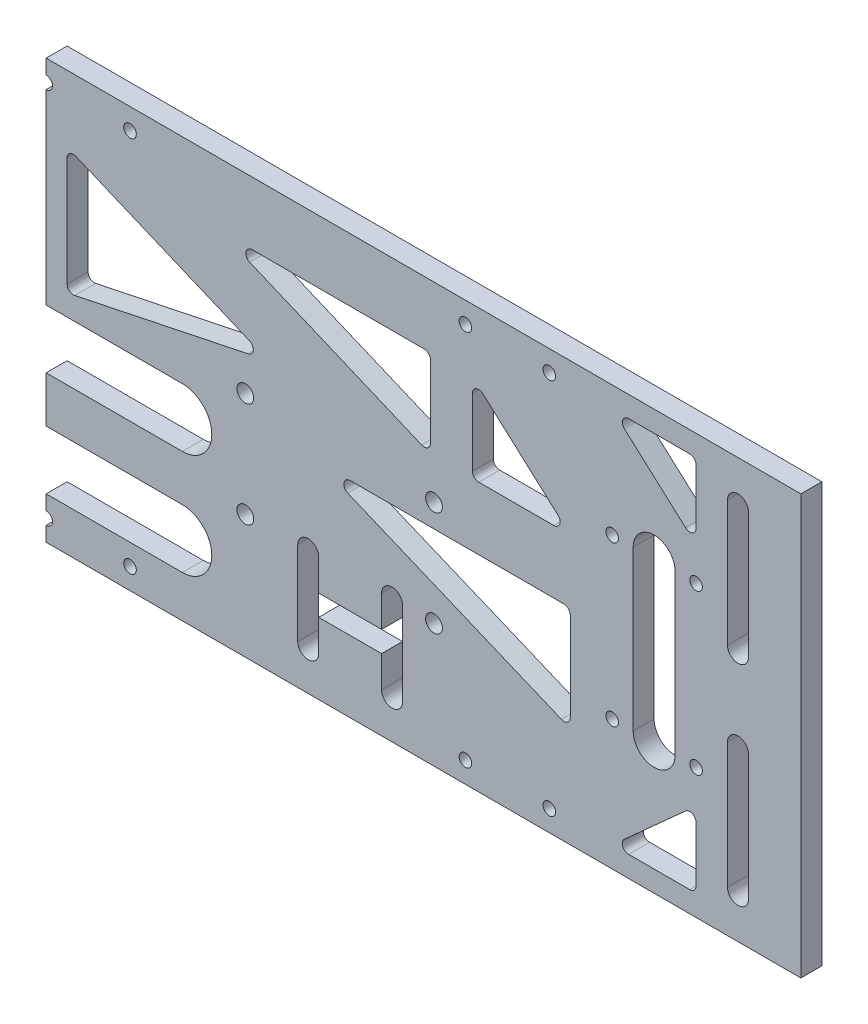
SolidWorks part; units mm, degrees
material "A-玻璃纤维"
ref_plane "前视基准面" through (0, 0, 0) normal (0, 0, 1) x (1, 0, 0)
ref_plane "上视基准面" through (0, 0, 0) normal (0, 1, 0) x (1, 0, 0)
ref_plane "右视基准面" through (0, 0, 0) normal (1, 0, 0) x (0, 0, -1)
sketch "草图1" plane through (0, 0, 0) normal (0, 0, 1) x (1, 0, 0)
  line L1 (0, 0) -> (320, 0)
  line L2 (0, 0) -> (0, 121)
  line L3 (0, 121) -> (320, 121)
  line L4 (320, 0) -> (320, 121)
  dimension "D1" = 320
  dimension "D2" = 121
extrude "凸台-拉伸1" add sketch "草图1" along normal blind 5
sketch "草图2" plane through (0, 0, 5) normal (0, 0, 1) x (1, 0, 0)
  line L0 (160, 121) -> (160, 0) construction
  line L1 (320, 121) -> (0, 121) construction
  line L2 (0, 0) -> (320, 0) construction
  line L3 (0, 121) -> (0, 0) construction
  line L4 (30, 0) -> (35, 0)
  line L5 (30, 0) -> (30, 30)
  line L6 (30, 30) -> (35, 30)
  line L7 (35, 0) -> (35, 30)
  line L8 (285, 0) -> (285, 30)
  line L9 (290, 30) -> (285, 30)
  line L10 (290, 0) -> (290, 30)
  line L11 (290, 0) -> (285, 0)
  dimension "D1" = 30
  dimension "D2" = 30
  dimension "D3" = 5
extrude "切除-拉伸1" cut sketch "草图2" against normal through all
sketch "草图3" plane through (0, 0, 5) normal (0, 0, 1) x (1, 0, 0)
  line L0 (40, 116) -> (60, 116) construction
  line L1 (160, 121) -> (160, 0) construction
  line L2 (320, 121) -> (0, 121) construction
  line L3 (35, 0) -> (285, 0) construction
  line L4 (140, 116) -> (160, 116) construction
  line L5 (0, 121) -> (0, 0) construction
  line L6 (280, 116) -> (260, 116) construction
  circle A0 centre (40, 116) radius 1.5
  circle A1 centre (60, 116) radius 1.5
  circle A2 centre (140, 116) radius 1.5
  circle A3 centre (160, 116) radius 1.5
  circle A4 centre (260, 116) radius 1.5
  circle A5 centre (280, 116) radius 1.5
  circle A6 centre (180, 116) radius 1.5
  dimension "D5" = 3
  dimension "D1" = 40
  dimension "D2" = 5
  dimension "D3" = 20
  dimension "D4" = 20
extrude "切除-拉伸2" cut sketch "草图3" against normal through all
sketch "草图4" plane through (0, 0, 5) normal (0, 0, 1) x (1, 0, 0)
  line L0 (160, 121) -> (160, 0) construction
  line L1 (5, 90) -> (25, 90) construction
  line L2 (5, 90) -> (5, 10) construction
  line L3 (5, 10) -> (25, 10) construction
  line L4 (25, 90) -> (25, 10) construction
  line L5 (320, 121) -> (0, 121) construction
  line L6 (35, 0) -> (285, 0) construction
  line L7 (0, 0) -> (30, 0) construction
  line L8 (0, 121) -> (0, 0) construction
  line L10 (295, 90) -> (295, 10) construction
  line L11 (315, 10) -> (295, 10) construction
  line L12 (315, 90) -> (315, 10) construction
  line L13 (315, 90) -> (295, 90) construction
  circle A0 centre (5, 90) radius 1.5
  circle A1 centre (25, 90) radius 1.5
  circle A2 centre (5, 10) radius 1.5
  circle A3 centre (25, 10) radius 1.5
  circle A4 centre (295, 10) radius 1.5
  circle A5 centre (315, 10) radius 1.5
  circle A6 centre (295, 90) radius 1.5
  circle A7 centre (315, 90) radius 1.5
  dimension "D5" = 3
  dimension "D1" = 10
  dimension "D2" = 80
  dimension "D3" = 5
  dimension "D4" = 20
extrude "切除-拉伸3" cut sketch "草图4" against normal through all
sketch "草图6" plane through (0, 0, 5) normal (0, 0, 1) x (1, 0, 0)
  line L0 (160, 121) -> (160, 0) construction
  line L1 (320, 121) -> (0, 121) construction
  line L2 (35, 0) -> (285, 0) construction
  line L3 (127.5, 63) -> (192.5, 63) construction
  line L4 (112.5, 50.5) -> (207.5, 50.5) construction
  line L5 (112.5, 50.5) -> (112.5, 75.5) construction
  line L6 (112.5, 75.5) -> (207.5, 75.5) construction
  line L7 (207.5, 50.5) -> (207.5, 75.5) construction
  line L8 (112.5, 50.5) -> (207.5, 75.5) construction
  line L9 (112.5, 75.5) -> (207.5, 50.5) construction
  line L10 (127.5, 70) -> (192.5, 70)
  line L11 (127.5, 56) -> (192.5, 56)
  circle A0 centre (112.5, 75.5) radius 2
  circle A1 centre (207.5, 75.5) radius 2
  circle A2 centre (207.5, 50.5) radius 2
  circle A3 centre (112.5, 50.5) radius 2
  arc A4 (127.5, 70) -> (127.5, 56) centre (127.5, 63) ccw
  arc A5 (192.5, 56) -> (192.5, 70) centre (192.5, 63) ccw
  point P6 (160, 63)
  point P17 (160, 63)
  dimension "D1" = 4
  dimension "D5" = 7
  dimension "D2" = 25
  dimension "D3" = 95
  dimension "D4" = 45.5
  dimension "D6" = 15
extrude "切除-拉伸5" cut sketch "草图6" against normal through all
sketch "草图5" plane through (0, 0, 5) normal (0, 0, 1) x (1, 0, 0)
  line L0 (5, 101.368) -> (5, 114.5)
  line L1 (6.5, 116) -> (21.0911, 116)
  line L2 (22.0945, 113.3851) -> (7.5034, 100.2531)
  line L6 (5, 90) -> (25, 90) construction
  line L7 (0, 121) -> (0, 0) construction
  line L8 (320, 121) -> (0, 121) construction
  line L9 (38.9089, 85) -> (56.8333, 85)
  line L10 (58.3333, 86.5) -> (58.3333, 102.632)
  line L11 (55.8299, 103.7469) -> (37.9055, 87.6149)
  line L12 (160, 121) -> (160, 0) construction
  line L13 (35, 0) -> (285, 0) construction
  line L14 (35, 68.5) -> (35, 47.25)
  line L15 (35, 0) -> (285, 0)
  line L16 (35, 0) -> (35, 30)
  line L17 (35, 30) -> (285, 30)
  line L18 (285, 0) -> (285, 30)
  line L19 (37.0769, 45.8654) -> (88.0769, 67.1154)
  line L20 (87.5, 70) -> (36.5, 70)
  line L24 (68.3333, 87.2569) -> (68.3333, 104.5)
  line L25 (69.8333, 106) -> (110.8883, 106)
  line L26 (111.4691, 103.117) -> (70.4142, 85.874)
  line L27 (111.7889, 84.0154) -> (153.1936, 75.3769)
  line L28 (155, 76.8453) -> (155, 102.8738)
  line L29 (152.9192, 104.2567) -> (111.5144, 86.8668)
  line L30 (315, 90) -> (295, 90) construction
  line L31 (167.0808, 104.2567) -> (208.4856, 86.8668)
  line L32 (165, 76.8453) -> (165, 102.8738)
  line L33 (208.2111, 84.0154) -> (166.8064, 75.3769)
  line L34 (208.5309, 103.117) -> (249.5858, 85.874)
  line L35 (250.1667, 106) -> (209.1117, 106)
  line L36 (251.6667, 87.2569) -> (251.6667, 104.5)
  line L40 (232.5, 70) -> (283.5, 70)
  line L41 (282.9231, 45.8654) -> (231.9231, 67.1154)
  line L42 (285, 68.5) -> (285, 47.25)
  line L43 (264.1701, 103.7469) -> (282.0945, 87.6149)
  line L44 (261.6667, 86.5) -> (261.6667, 102.632)
  line L45 (281.0911, 85) -> (263.1667, 85)
  line L46 (297.9055, 113.3851) -> (312.4966, 100.2531)
  line L47 (313.5, 116) -> (298.9089, 116)
  line L48 (315, 101.368) -> (315, 114.5)
  line L52 (192.5, 70) -> (127.5, 70) construction
  arc A2 (155, 102.8738) -> (152.9192, 104.2567) centre (153.5, 102.8738) ccw
  arc A4 (21.0911, 116) -> (22.0945, 113.3851) centre (21.0911, 114.5) cw
  arc A5 (5, 101.368) -> (7.5034, 100.2531) centre (6.5, 101.368) ccw
  arc A6 (5, 114.5) -> (6.5, 116) centre (6.5, 114.5) cw
  arc A7 (56.8333, 85) -> (58.3333, 86.5) centre (56.8333, 86.5) ccw
  arc A8 (38.9089, 85) -> (37.9055, 87.6149) centre (38.9089, 86.5) cw
  arc A9 (58.3333, 102.632) -> (55.8299, 103.7469) centre (56.8333, 102.632) ccw
  arc A10 (88.0769, 67.1154) -> (87.5, 70) centre (87.5, 68.5) ccw
  arc A11 (35, 47.25) -> (37.0769, 45.8654) centre (36.5, 47.25) ccw
  arc A12 (35, 68.5) -> (36.5, 70) centre (36.5, 68.5) cw
  arc A17 (153.1936, 75.3769) -> (155, 76.8453) centre (153.5, 76.8453) ccw
  arc A18 (111.7889, 84.0154) -> (111.5144, 86.8668) centre (112.0953, 85.4838) cw
  arc A19 (68.3333, 87.2569) -> (70.4142, 85.874) centre (69.8333, 87.2569) ccw
  arc A20 (68.3333, 104.5) -> (69.8333, 106) centre (69.8333, 104.5) cw
  arc A21 (110.8883, 106) -> (111.4691, 103.117) centre (110.8883, 104.5) cw
  arc A22 (209.1117, 106) -> (208.5309, 103.117) centre (209.1117, 104.5) ccw
  arc A23 (251.6667, 104.5) -> (250.1667, 106) centre (250.1667, 104.5) ccw
  arc A24 (251.6667, 87.2569) -> (249.5858, 85.874) centre (250.1667, 87.2569) cw
  arc A25 (208.2111, 84.0154) -> (208.4856, 86.8668) centre (207.9047, 85.4838) ccw
  arc A26 (166.8064, 75.3769) -> (165, 76.8453) centre (166.5, 76.8453) cw
  arc A30 (285, 68.5) -> (283.5, 70) centre (283.5, 68.5) ccw
  arc A31 (285, 47.25) -> (282.9231, 45.8654) centre (283.5, 47.25) cw
  arc A32 (231.9231, 67.1154) -> (232.5, 70) centre (232.5, 68.5) cw
  arc A33 (261.6667, 102.632) -> (264.1701, 103.7469) centre (263.1667, 102.632) cw
  arc A34 (281.0911, 85) -> (282.0945, 87.6149) centre (281.0911, 86.5) ccw
  arc A35 (263.1667, 85) -> (261.6667, 86.5) centre (263.1667, 86.5) cw
  arc A36 (315, 114.5) -> (313.5, 116) centre (313.5, 114.5) ccw
  arc A37 (315, 101.368) -> (312.4966, 100.2531) centre (313.5, 101.368) cw
  arc A38 (298.9089, 116) -> (297.9055, 113.3851) centre (298.9089, 114.5) ccw
  arc A39 (165, 102.8738) -> (167.0808, 104.2567) centre (166.5, 102.8738) cw
  point P23 (25, 116)
  point P26 (5, 98)
  point P29 (5, 116)
  point P40 (35, 85)
  point P43 (58.3333, 106)
  point P56 (95, 70)
  point P59 (35, 45)
  point P62 (35, 70)
  point P84 (155, 105.1307)
  point P87 (155, 75)
  point P90 (107.0698, 85)
  point P93 (68.3333, 85)
  point P96 (68.3333, 106)
  point P99 (118.3333, 106)
  point P156 (201.6667, 106)
  point P157 (251.6667, 106)
  point P158 (251.6667, 85)
  point P159 (212.9302, 85)
  point P160 (165, 75)
  point P161 (165, 105.1307)
  point P162 (285, 70)
  point P163 (285, 45)
  point P164 (225, 70)
  point P165 (261.6667, 106)
  point P166 (285, 85)
  point P167 (315, 116)
  point P168 (315, 98)
  point P169 (295, 116)
  point P186 (20, 15)
  point P189 (8, 15)
  point P192 (20, 25)
  point P202 (300, 25)
  point P203 (312, 15)
  point P204 (300, 15)
  dimension "D8" = 1.5
  dimension "D12" = 1.5
  dimension "D16" = 1.5
  dimension "D27" = 1.5
  dimension "D4" = 5
  dimension "D5" = 5
  dimension "D6" = 20
  dimension "D7" = 18
  dimension "D9" = 5
  dimension "D10" = 10
  dimension "D11" = 10
  dimension "D13" = 15
  dimension "D14" = 15
  dimension "D15" = 60
  dimension "D21" = 15
  dimension "D22" = 10
  dimension "D23" = 50
  dimension "D24" = 15
  dimension "D25" = 10
  dimension "D26" = 5
  dimension "D29" = 8
  dimension "D31" = 10
extrude "切除-拉伸4" cut sketch "草图5" against normal through all
sketch "草图7" plane through (0, 0, 0) normal (0, 0, -1) x (-1, 0, 0)
  line L0 (-290, 0) -> (-290, 30)
  line L1 (-290, 30) -> (-30, 30)
  line L2 (-30, 30) -> (-30, 0)
  line L3 (-30, 0) -> (-290, 0)
extrude "凸台-拉伸2" add sketch "草图7" against normal blind 5
sketch "草图8" plane through (0, 0, 0) normal (0, 0, -1) x (-1, 0, 0)
  line L0 (-320, 0) -> (-320, 21)
  line L1 (-320, 0) -> (-320, 121) construction
  line L2 (-320, 21) -> (0, 21)
  line L3 (0, 121) -> (0, 0) construction
  line L4 (0, 21) -> (0, 0)
  line L5 (0, 0) -> (-320, 0)
extrude "切除-拉伸6" cut sketch "草图8" against normal blind 5
sketch "草图9" plane through (0, 0, 0) normal (0, 0, -1) x (-1, 0, 0)
  line L0 (-160, 21) -> (-335, 21)
  line L1 (0, 21) -> (-320, 21) construction
  line L2 (-335, 21) -> (-335, 121)
  line L3 (-335, 121) -> (15, 121)
  line L4 (15, 121) -> (15, 21)
  line L5 (15, 21) -> (-160, 21)
  line L6 (0, 21) -> (0, 121)
  line L7 (-320, 21) -> (-320, 121)
extrude "凸台-拉伸3" add sketch "草图9" against normal blind 5 contours L0 L7 L3 L2 | L6 L5 L4 L3
sketch "草图10" plane through (0, 0, 0) normal (0, 0, -1) x (-1, 0, 0)
  line L0 (-335, 71) -> (-325, 71)
  line L1 (-335, 21) -> (-335, 121) construction
  line L2 (-325, 71) -> (-325, 121)
  line L3 (-335, 121) -> (15, 121) construction
  line L4 (-325, 71) -> (-325, 21)
  line L5 (15, 21) -> (-335, 21) construction
  line L6 (15, 71) -> (5, 71)
  line L7 (15, 121) -> (15, 21) construction
  line L8 (5, 71) -> (5, 121)
  line L9 (5, 71) -> (5, 21)
  line L10 (-325, 71) -> (-325, 81)
  line L11 (-325, 81) -> (-325, 111)
  line L12 (-325, 71) -> (-325, 61)
  line L13 (-325, 61) -> (-325, 31)
  line L14 (-325, 81) -> (-325, 111) construction
  line L15 (-327.5, 81) -> (-327.5, 111)
  line L16 (-322.5, 81) -> (-322.5, 111)
  line L17 (-325, 61) -> (-325, 31) construction
  line L18 (-322.5, 61) -> (-322.5, 31)
  line L19 (-327.5, 61) -> (-327.5, 31)
  line L20 (-160, 21) -> (-160, 121)
  line L21 (5, 61) -> (5, 31) construction
  line L22 (2.5, 61) -> (2.5, 31)
  line L23 (7.5, 61) -> (7.5, 31)
  line L24 (5, 81) -> (5, 111) construction
  line L25 (7.5, 81) -> (7.5, 111)
  line L26 (2.5, 81) -> (2.5, 111)
  arc A0 (-327.5, 81) -> (-322.5, 81) centre (-325, 81) ccw
  arc A1 (-322.5, 111) -> (-327.5, 111) centre (-325, 111) ccw
  arc A2 (-322.5, 61) -> (-327.5, 61) centre (-325, 61) ccw
  arc A3 (-327.5, 31) -> (-322.5, 31) centre (-325, 31) ccw
  arc A4 (2.5, 61) -> (7.5, 61) centre (5, 61) cw
  arc A5 (7.5, 31) -> (2.5, 31) centre (5, 31) cw
  arc A6 (7.5, 81) -> (2.5, 81) centre (5, 81) cw
  arc A7 (2.5, 111) -> (7.5, 111) centre (5, 111) cw
  point P20 (-325, 96)
  point P25 (-325, 46)
  point P34 (5, 46)
  point P41 (5, 96)
  dimension "D1" = 10
  dimension "D2" = 10
  dimension "D3" = 30
  dimension "D4" = 10
  dimension "D5" = 30
extrude "切除-拉伸7" cut sketch "草图10" against normal blind 5 contours L16 A1 L2 L10 A0 | L2 A1 L15 A0 L10 | L4 A3 L18 A2 L12 | L19 A3 L4 L12 A2 | A7 L8 A6 L25 | A7 L26 A6 L8 | A5 L23 A4 L9 | A5 L9 A4 L22
sketch "草图13" plane through (0, 0, 0) normal (0, 0, -1) x (-1, 0, 0)
  line L12 (-192.5, 63) -> (-192.5, 38)
  line L13 (-127.5, 63) -> (-127.5, 38)
  line L14 (-192.5, 38) -> (-127.5, 38) construction
  line L15 (-192.5, 45) -> (-127.5, 45)
  line L16 (-192.5, 31) -> (-127.5, 31)
  line L18 (-305, 63.5) -> (-305, 83.5)
  line L19 (-305, 63.5) -> (-305, 48.5)
  line L23 (-160, 21) -> (-160, 121)
  line L24 (15, 21) -> (-335, 21) construction
  line L25 (-335, 121) -> (15, 121) construction
  arc A1 (-192.5, 45) -> (-192.5, 31) centre (-192.5, 38) ccw
  arc A2 (-127.5, 31) -> (-127.5, 45) centre (-127.5, 38) ccw
  point P16 (-160, 38)
  dimension "D1" = 25
  dimension "D3" = 15
  dimension "D2" = 25
  dimension "D4" = 20
extrude "切除-拉伸8" cut sketch "草图13" against normal blind 5
sketch "草图15" plane through (0, 0, 0) normal (0, 0, -1) x (-1, 0, 0)
  line L0 (-313.5, 116) -> (-298.9089, 116)
  line L1 (-297.9055, 113.3851) -> (-312.4966, 100.2531)
  line L2 (-315, 114.5) -> (-315, 101.368)
  line L3 (-21.0911, 116) -> (-6.5, 116)
  line L4 (-5, 114.5) -> (-5, 101.368)
  line L5 (-7.5034, 100.2531) -> (-22.0945, 113.3851)
  line L6 (-335, 71) -> (15, 71)
  line L7 (-335, 21) -> (-335, 121) construction
  line L8 (15, 121) -> (15, 21) construction
  line L9 (-21.0911, 26) -> (-6.5, 26)
  line L10 (-5, 27.5) -> (-5, 40.632)
  line L11 (-7.5034, 41.7469) -> (-22.0945, 28.6149)
  line L12 (-315, 27.5) -> (-315, 40.632)
  line L13 (-313.5, 26) -> (-298.9089, 26)
  line L14 (-297.9055, 28.6149) -> (-312.4966, 41.7469)
  circle A0 centre (-280, 116) radius 1.5
  circle A1 centre (-260, 116) radius 1.5
  circle A2 centre (-180, 116) radius 1.5
  circle A3 centre (-160, 116) radius 1.5
  circle A4 centre (-140, 116) radius 1.5
  circle A5 centre (-60, 116) radius 1.5
  circle A6 centre (-40, 116) radius 1.5
  circle A7 centre (-25, 90) radius 1.5
  circle A8 centre (-5, 90) radius 1.5
  circle A9 centre (-315, 90) radius 1.5
  circle A10 centre (-295, 90) radius 1.5
  arc A11 (-315, 101.368) -> (-312.4966, 100.2531) centre (-313.5, 101.368) ccw
  arc A12 (-313.5, 116) -> (-315, 114.5) centre (-313.5, 114.5) ccw
  arc A13 (-297.9055, 113.3851) -> (-298.9089, 116) centre (-298.9089, 114.5) ccw
  arc A14 (-21.0911, 116) -> (-22.0945, 113.3851) centre (-21.0911, 114.5) ccw
  arc A15 (-5, 114.5) -> (-6.5, 116) centre (-6.5, 114.5) ccw
  arc A16 (-7.5034, 100.2531) -> (-5, 101.368) centre (-6.5, 101.368) ccw
  circle A17 centre (-25, 52) radius 1.5
  circle A18 centre (-5, 52) radius 1.5
  arc A19 (-5, 27.5) -> (-6.5, 26) centre (-6.5, 27.5) cw
  arc A20 (-7.5034, 41.7469) -> (-5, 40.632) centre (-6.5, 40.632) cw
  arc A21 (-21.0911, 26) -> (-22.0945, 28.6149) centre (-21.0911, 27.5) cw
  circle A22 centre (-40, 26) radius 1.5
  circle A23 centre (-60, 26) radius 1.5
  circle A24 centre (-140, 26) radius 1.5
  circle A25 centre (-160, 26) radius 1.5
  circle A26 centre (-180, 26) radius 1.5
  circle A27 centre (-260, 26) radius 1.5
  circle A28 centre (-280, 26) radius 1.5
  arc A29 (-313.5, 26) -> (-315, 27.5) centre (-313.5, 27.5) cw
  arc A30 (-297.9055, 28.6149) -> (-298.9089, 26) centre (-298.9089, 27.5) cw
  arc A31 (-315, 40.632) -> (-312.4966, 41.7469) centre (-313.5, 40.632) cw
  circle A32 centre (-295, 52) radius 1.5
  circle A33 centre (-315, 52) radius 1.5
extrude "切除-拉伸9" cut sketch "草图15" against normal through all contours A33 | A31 L12 A29 L13 A30 L14 | A32 | A28 | A27 | A26 | A25 | A24 | A23 | A22 | A21 L9 A19 L10 A20 L11 | A18 | A17
sketch "草图16" plane through (0, 0, 0) normal (0, 0, -1) x (-1, 0, 0)
  line L0 (-335, 71) -> (15, 71)
  line L1 (-335, 21) -> (-335, 121) construction
  line L2 (15, 121) -> (15, 21) construction
  line L3 (-315, 90) -> (-295, 90)
  line L4 (-315, 52) -> (-295, 52)
  line L5 (-305, 52) -> (-305, 90)
  line L6 (-305, 52) -> (-305, 90) construction
  line L7 (-310, 52) -> (-310, 90)
  line L8 (-300, 52) -> (-300, 90)
  line L9 (-160, 21) -> (-160, 121)
  line L10 (15, 21) -> (-335, 21) construction
  line L11 (-335, 121) -> (15, 121) construction
  line L12 (-15, 52) -> (-15, 90) construction
  line L13 (-10, 52) -> (-10, 90)
  line L14 (-20, 52) -> (-20, 90)
  arc A0 (-310, 52) -> (-300, 52) centre (-305, 52) ccw
  arc A1 (-300, 90) -> (-310, 90) centre (-305, 90) ccw
  arc A2 (-10, 52) -> (-20, 52) centre (-15, 52) cw
  arc A3 (-20, 90) -> (-10, 90) centre (-15, 90) cw
  point P16 (-305, 71)
  point P29 (-15, 71)
extrude "切除-拉伸10" cut sketch "草图16" against normal through all contours L4 L8 L0 L5 | L4 A0 | L7 L4 L5 L0 | L0 L8 L3 L5 | L7 L0 L5 L3 | L3 A1 | A2 L13 L0 L14 | A3 L14 L0 L13
sketch "草图17" plane through (0, 0, 0) normal (0, 0, -1) x (-1, 0, 0)
  line L0 (-207.5, 50.5) -> (-257.5, 50.5)
  line L1 (-257.5, 50.5) -> (-257.5, 30.5)
  line L2 (-257.5, 30.5) -> (-207.5, 30.5)
  line L3 (-207.5, 30.5) -> (-207.5, 50.5)
  line L4 (-207.5, 40.5) -> (-257.5, 40.5)
  line L5 (-257.5, 50.5) -> (-247.5, 50.5)
  line L6 (-247.5, 50.5) -> (-247.5, 30.5)
  line L7 (-207.5, 50.5) -> (-217.5, 50.5)
  line L8 (-217.5, 50.5) -> (-217.5, 30.5)
  line L9 (-247.5, 50.5) -> (-242.5, 50.5)
  line L10 (-242.5, 50.5) -> (-242.5, 30.5)
  line L11 (-217.5, 50.5) -> (-222.5, 50.5)
  line L12 (-222.5, 50.5) -> (-222.5, 30.5)
  line L13 (-242.5, 50.5) -> (-242.5, 30.5) construction
  line L14 (-240, 50.5) -> (-240, 30.5)
  line L15 (-245, 50.5) -> (-245, 30.5)
  line L16 (-222.5, 50.5) -> (-222.5, 30.5) construction
  line L17 (-220, 50.5) -> (-220, 30.5)
  line L18 (-225, 50.5) -> (-225, 30.5)
  line L19 (-242.5, 40.5) -> (-222.5, 40.5) construction
  line L20 (-242.5, 43) -> (-222.5, 43)
  line L21 (-242.5, 38) -> (-222.5, 38)
  line L22 (-160, 21) -> (-160, 121)
  line L23 (15, 21) -> (-335, 21) construction
  line L24 (-335, 121) -> (15, 121) construction
  line L25 (-97.5, 50.5) -> (-97.5, 30.5) construction
  line L26 (-100, 50.5) -> (-100, 30.5)
  line L27 (-95, 50.5) -> (-95, 30.5)
  line L28 (-77.5, 40.5) -> (-97.5, 40.5) construction
  line L29 (-77.5, 43) -> (-97.5, 43)
  line L30 (-77.5, 38) -> (-97.5, 38)
  line L31 (-77.5, 50.5) -> (-77.5, 30.5) construction
  line L32 (-80, 50.5) -> (-80, 30.5)
  line L33 (-75, 50.5) -> (-75, 30.5)
  arc A0 (-240, 50.5) -> (-245, 50.5) centre (-242.5, 50.5) ccw
  arc A1 (-245, 30.5) -> (-240, 30.5) centre (-242.5, 30.5) ccw
  arc A2 (-220, 50.5) -> (-225, 50.5) centre (-222.5, 50.5) ccw
  arc A3 (-225, 30.5) -> (-220, 30.5) centre (-222.5, 30.5) ccw
  arc A4 (-242.5, 43) -> (-242.5, 38) centre (-242.5, 40.5) ccw
  arc A5 (-222.5, 38) -> (-222.5, 43) centre (-222.5, 40.5) ccw
  arc A6 (-100, 50.5) -> (-95, 50.5) centre (-97.5, 50.5) cw
  arc A7 (-95, 30.5) -> (-100, 30.5) centre (-97.5, 30.5) cw
  arc A8 (-77.5, 43) -> (-77.5, 38) centre (-77.5, 40.5) cw
  arc A9 (-97.5, 38) -> (-97.5, 43) centre (-97.5, 40.5) cw
  arc A10 (-80, 50.5) -> (-75, 50.5) centre (-77.5, 50.5) cw
  arc A11 (-75, 30.5) -> (-80, 30.5) centre (-77.5, 30.5) cw
  point P11 (-242.5, 40.5)
  point P20 (-222.5, 40.5)
  point P25 (-232.5, 40.5)
  point P40 (-97.5, 40.5)
  point P47 (-87.5, 40.5)
  point P54 (-77.5, 40.5)
  dimension "D1" = 20
extrude "切除-拉伸11" cut sketch "草图17" against normal through all contours A11 L33 A8 L30 L32 | A8 L29 L32 L30 | A10 L32 L29 A8 L33 | L32 L29 L27 L30 | A9 L30 L27 L29 | L26 A9 L29 L27 A6 | L30 A9 L26 A7 L27 | L10 L20 L14 L0 | A4 L10 L0 L15 | L0 A0 | L20 L14 L4 L18 | L20 L10 L4 L14 | L10 A4 L4 | L4 A4 L10 | L10 L21 L14 L4 | L14 L21 L18 L4 | L21 L10 L2 L14 | A4 L15 L2 L10 | L2 A1 | L2 A3 | A5 L12 L2 L17 | L21 L18 L2 L12 | L18 L21 L12 L4 | L12 A5 L4 | L4 A5 L12 | L20 L18 L4 L12 | L18 L20 L12 L0 | A5 L17 L11 L12 | L11 A2 L0
sketch "草图18" plane through (0, 0, 0) normal (0, 0, -1) x (-1, 0, 0)
  line L0 (-335, 21) -> (-340, 21)
  line L1 (-340, 21) -> (-340, 121)
  line L2 (-340, 121) -> (-335, 121)
  line L3 (-335, 121) -> (-335, 21)
  line L4 (15, 21) -> (20, 21)
  line L5 (20, 21) -> (20, 121)
  line L6 (20, 121) -> (15, 121)
  line L7 (15, 121) -> (15, 21)
extrude "凸台-拉伸4" add sketch "草图18" against normal blind 5
sketch "草图19" plane through (0, 0, 5) normal (0, 0, 1) x (1, 0, 0)
  line L0 (160, 121) -> (160, 21)
  line L1 (340, 121) -> (-20, 121) construction
  line L2 (-20, 21) -> (340, 21) construction
  line L3 (160, 21) -> (340, 21)
  line L4 (340, 21) -> (340, 121)
  line L5 (340, 121) -> (160, 121)
  line L6 (160, 121) -> (-20, 121)
  line L7 (-20, 121) -> (-20, 21)
  line L8 (-20, 21) -> (160, 21)
extrude "切除-拉伸12" cut sketch "草图19" against normal blind 10 contours L7 L8 L0 L6
sketch "草图20" plane through (0, 0, 5) normal (0, 0, 1) x (1, 0, 0)
  line L0 (207.5, 75.5) -> (252.5, 75.5)
  line L1 (207.5, 50.5) -> (252.5, 50.5)
  circle A0 centre (252.5, 75.5) radius 2
  circle A1 centre (252.5, 50.5) radius 2
extrude "切除-拉伸13" cut sketch "草图20" against normal blind 10
